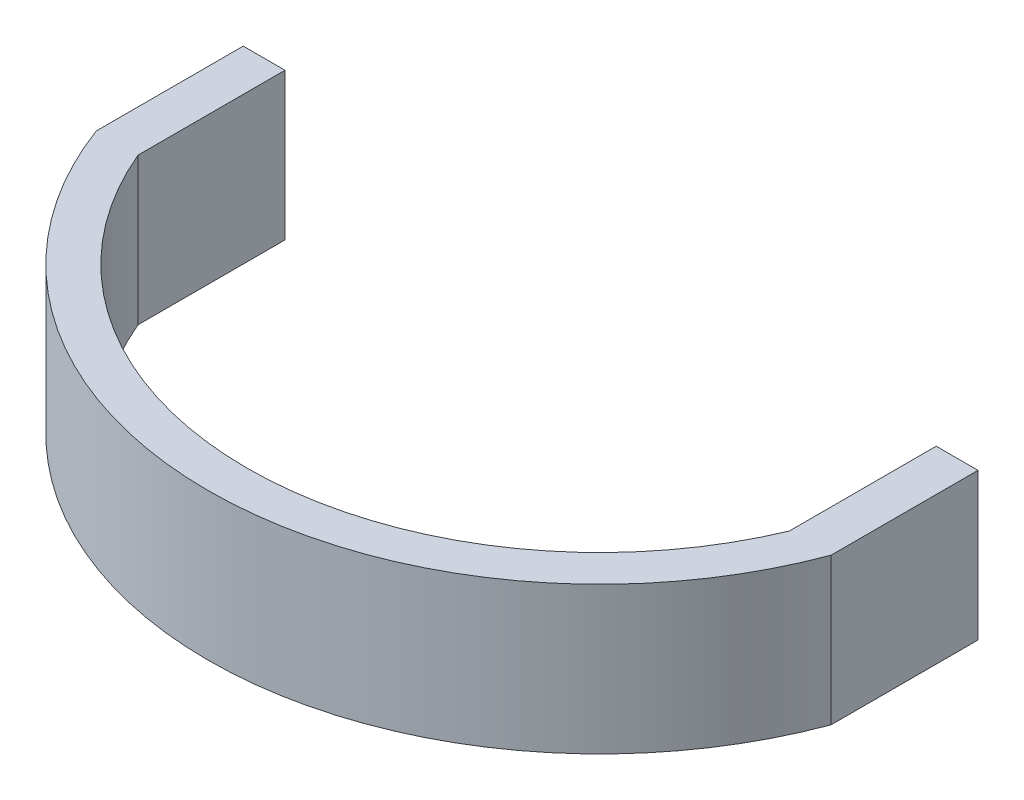
SolidWorks part; units mm, degrees
material "1060 Alloy"
ref_plane "Front Plane" through (0, 0, 0) normal (0, 0, 1) x (1, 0, 0)
ref_plane "Top Plane" through (0, 0, 0) normal (0, 1, 0) x (1, 0, 0)
ref_plane "Right Plane" through (0, 0, 0) normal (1, 0, 0) x (0, 0, -1)
sketch "Sketch1" plane through (0, 0, 0) normal (0, 1, 0) x (1, 0, 0)
  line L0 (-7.5, -2.7839) -> (-7.5, 0.2161)
  line L1 (-7.5, 0.2161) -> (-6.6468, 0.2161)
  line L2 (-6.6468, 0.2161) -> (-6.6468, -2.7839)
  line L3 (6.6468, -2.7839) -> (6.6468, 0.2161)
  line L4 (6.6468, 0.2161) -> (7.5, 0.2161)
  line L5 (7.5, 0.2161) -> (7.5, -2.7839)
  arc A0 (-7.5, -2.7839) -> (7.5, -2.7839) centre (0, 0) ccw
  arc A1 (-6.6468, -2.7839) -> (6.6468, -2.7839) centre (0, 0) ccw
  dimension "D1" = 8
  dimension "D2" = 0.7937
  dimension "D3" = 3
  dimension "D4" = 15
extrude "Boss-Extrude1" add sketch "Sketch1" along normal mid plane 3
